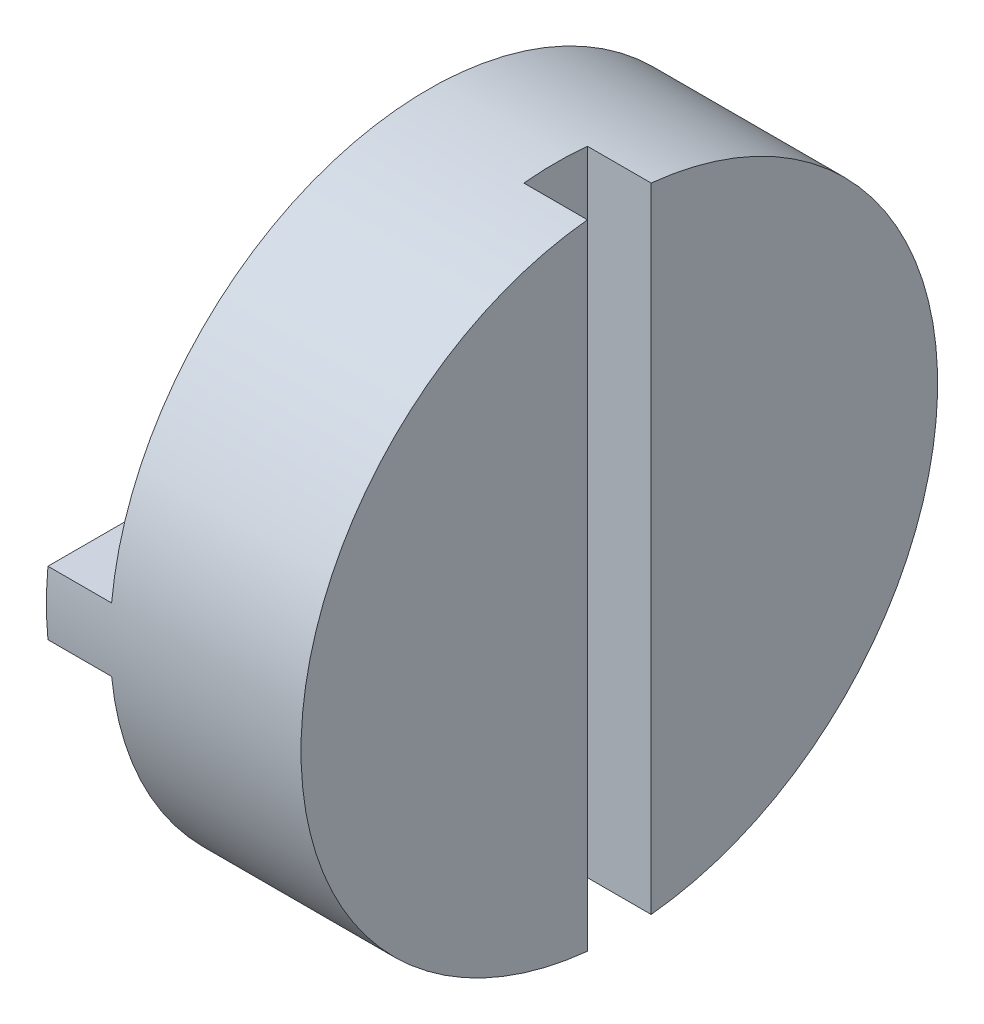
SolidWorks part; units mm, degrees
ref_plane "Front Plane" through (0, 0, 0) normal (0, 0, 1) x (1, 0, 0)
ref_plane "Top Plane" through (0, 0, 0) normal (0, 1, 0) x (1, 0, 0)
ref_plane "Right Plane" through (0, 0, 0) normal (1, 0, 0) x (0, 0, -1)
sketch "Sketch1" plane through (0, 0, 0) normal (1, 0, 0) x (0, 0, -1)
  circle A0 centre (0, 0) radius 25
  dimension "D1" = 50
extrude "Boss-Extrude1" add sketch "Sketch1" along normal blind 10 and the other way blind 5
sketch "Sketch2" plane through (10, 0, 0) normal (1, 0, 0) x (0, 0, -1)
  line L2 (2.5, 24.8747) -> (2.5, -24.8747)
  line L4 (-2.5, 24.8747) -> (-2.5, -24.8747)
  line L5 (2.2778, 24.896) -> (-2.2778, -24.896) construction
  line L6 (2.2778, -24.896) -> (-2.2778, 24.896) construction
  circle A0 centre (0, 0) radius 25 construction
  arc A1 (-2.5, -24.8747) -> (2.5, -24.8747) centre (0, 0) ccw
  arc A2 (2.5, 24.8747) -> (-2.5, 24.8747) centre (0, 0) ccw
  point P0 (0, 0)
extrude "Cut-Extrude1" cut sketch "Sketch2" against normal blind 5
sketch "Sketch4" plane through (-5, 0, 0) normal (-1, 0, 0) x (0, 0, 1)
  line L1 (-24.8747, -2.5) -> (24.8747, -2.5)
  line L3 (-24.8747, 2.5) -> (24.8747, 2.5)
  line L5 (-24.8993, -2.2413) -> (24.8993, 2.2413) construction
  line L6 (-24.8993, 2.2413) -> (24.8993, -2.2413) construction
  circle A0 centre (0, 0) radius 25 construction
  arc A1 (24.8747, -2.5) -> (24.8747, 2.5) centre (0, 0) ccw
  arc A2 (-24.8747, 2.5) -> (-24.8747, -2.5) centre (0, 0) ccw
  point P0 (0, 0)
extrude "Boss-Extrude2" add sketch "Sketch4" along normal blind 5
